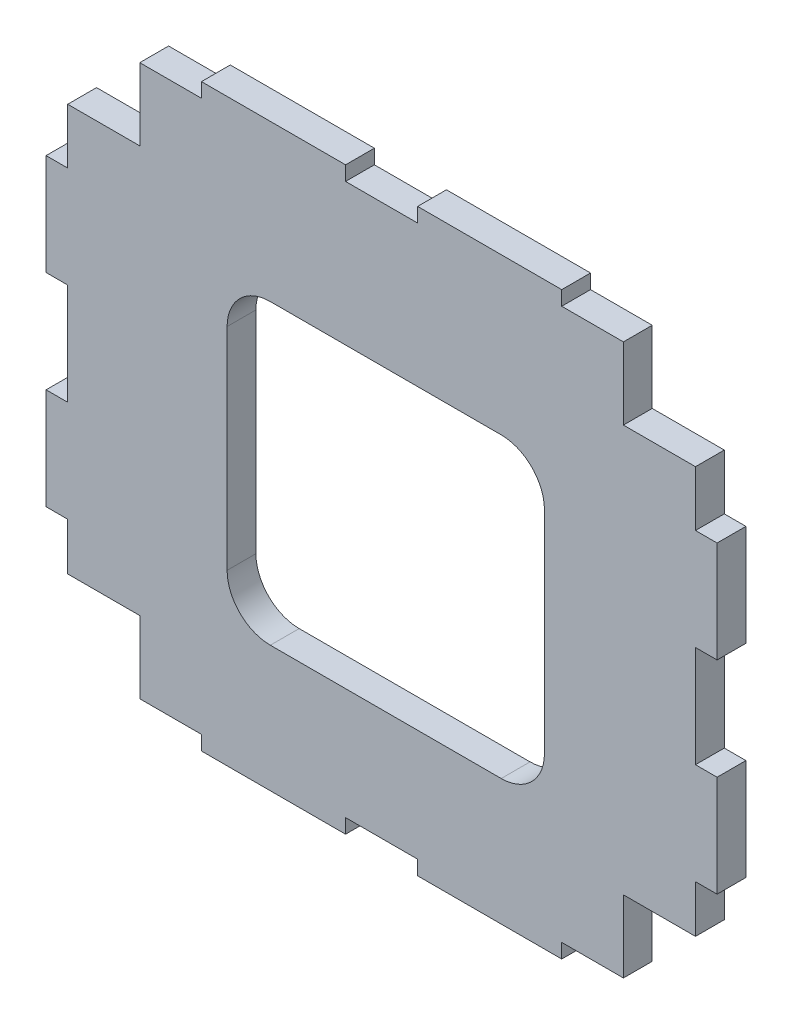
SolidWorks part; units mm, degrees
ref_plane "前视基准面" through (0, 0, 0) normal (0, 0, 1) x (1, 0, 0)
ref_plane "上视基准面" through (0, 0, 0) normal (0, 1, 0) x (1, 0, 0)
ref_plane "右视基准面" through (0, 0, 0) normal (1, 0, 0) x (0, 0, -1)
sketch "Model" plane through (0, 0, 0) normal (0, 0, 1) x (1, 0, 0)
  line L0 (27.7711, 46.6664) -> (32.0511, 46.6664)
  line L1 (32.0511, 46.6664) -> (32.0511, 47.6668)
  line L2 (32.0511, 47.6668) -> (42.0511, 47.6668)
  line L3 (42.0511, 47.6668) -> (42.0511, 46.6664)
  line L4 (42.0511, 46.6664) -> (47.0511, 46.6664)
  line L5 (47.0511, 46.6664) -> (47.0511, 47.6668)
  line L6 (47.0511, 47.6668) -> (57.0511, 47.6668)
  line L7 (57.0511, 47.6668) -> (57.0511, 46.6664)
  line L8 (57.0511, 46.6664) -> (61.3311, 46.6664)
  line L9 (27.7711, 8.4395) -> (32.0511, 8.4395)
  line L10 (32.0511, 8.4395) -> (32.0511, 7.4392)
  line L11 (32.0511, 7.4392) -> (42.0511, 7.4392)
  line L12 (42.0511, 7.4392) -> (42.0511, 8.4395)
  line L13 (42.0511, 8.4395) -> (47.0511, 8.4395)
  line L14 (47.0511, 8.4395) -> (47.0511, 7.4392)
  line L15 (47.0511, 7.4392) -> (57.0511, 7.4392)
  line L16 (57.0511, 7.4392) -> (57.0511, 8.4395)
  line L17 (57.0511, 8.4395) -> (61.3311, 8.4395)
  line L18 (27.7711, 46.6664) -> (27.7711, 41.6664)
  line L19 (27.7711, 41.6664) -> (22.7711, 41.6664)
  line L20 (22.7711, 41.6664) -> (22.7711, 37.8307)
  line L21 (22.7711, 37.8307) -> (21.2711, 37.8307)
  line L23 (21.2711, 30.8307) -> (22.7711, 30.8307)
  line L24 (21.2711, 37.8471) -> (21.2711, 30.8017)
  line L25 (21.2711, 30.8017) -> (22.7711, 30.8017)
  line L26 (22.7711, 30.8017) -> (22.7711, 23.7563)
  line L27 (27.7711, 8.4395) -> (27.7711, 13.4395)
  line L28 (27.7711, 13.4395) -> (22.7711, 13.4395)
  line L29 (22.7711, 13.4395) -> (22.7711, 16.7274)
  line L30 (22.7711, 16.7274) -> (21.2711, 16.7274)
  line L32 (21.2711, 23.7274) -> (22.7711, 23.7274)
  line L33 (21.2711, 16.711) -> (21.2711, 23.7563)
  line L34 (21.2711, 23.7563) -> (22.7711, 23.7563)
  line L35 (61.3311, 46.6664) -> (61.3311, 41.6664)
  line L36 (61.3311, 41.6664) -> (66.3311, 41.6664)
  line L37 (66.3311, 41.6664) -> (66.3311, 37.8307)
  line L38 (66.3311, 37.8307) -> (67.8311, 37.8307)
  line L40 (67.8311, 30.8307) -> (66.3311, 30.8307)
  line L41 (67.8311, 37.8471) -> (67.8311, 30.8017)
  line L42 (67.8311, 30.8017) -> (66.3311, 30.8017)
  line L43 (66.3311, 30.8017) -> (66.3311, 23.7563)
  line L44 (61.3311, 8.4395) -> (61.3311, 13.4395)
  line L45 (61.3311, 13.4395) -> (66.3311, 13.4395)
  line L46 (66.3311, 13.4395) -> (66.3311, 16.7274)
  line L47 (66.3311, 16.7274) -> (67.8311, 16.7274)
  line L49 (67.8311, 23.7274) -> (66.3311, 23.7274)
  line L50 (67.8311, 16.711) -> (67.8311, 23.7563)
  line L51 (67.8311, 23.7563) -> (66.3311, 23.7563)
  line L52 (52.8519, 36.8381) -> (36.8319, 36.8381)
  line L53 (36.8319, 16.1881) -> (52.8519, 16.1881)
  line L54 (55.8519, 33.8381) -> (55.8519, 19.1881)
  line L55 (33.8319, 33.8381) -> (33.8319, 19.1881)
  arc A0 (36.8319, 36.8381) -> (33.8319, 33.8381) centre (36.8319, 33.8381) ccw
  arc A1 (52.8519, 16.1881) -> (55.8519, 19.1881) centre (52.8519, 19.1881) ccw
  arc A2 (55.8519, 33.8381) -> (52.8519, 36.8381) centre (52.8519, 33.8381) ccw
  arc A3 (33.8319, 19.1881) -> (36.8319, 16.1881) centre (36.8319, 19.1881) ccw
extrude "凸台-拉伸1" add sketch "Model" along normal blind 2
